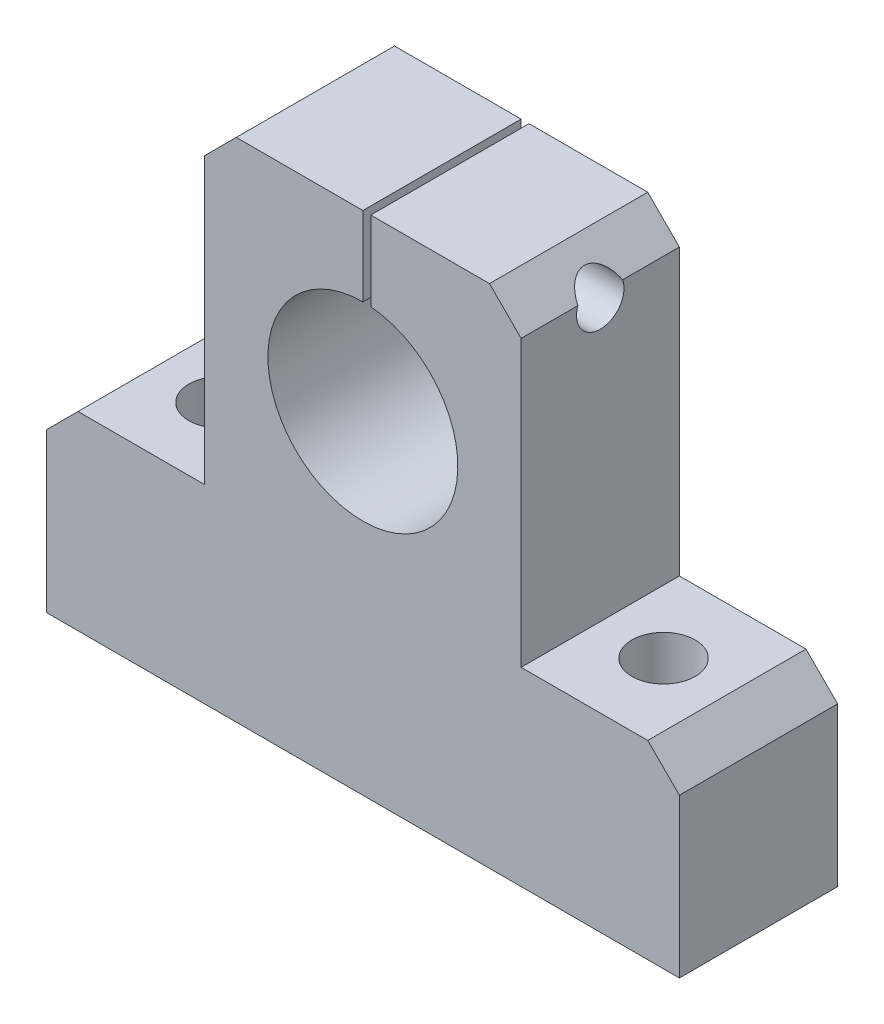
SolidWorks part; units mm, degrees
ref_plane "Front Plane" through (0, 0, 0) normal (0, 0, 1) x (1, 0, 0)
ref_plane "Top Plane" through (0, 0, 0) normal (0, 1, 0) x (1, 0, 0)
ref_plane "Right Plane" through (0, 0, 0) normal (1, 0, 0) x (0, 0, -1)
sketch "Sketch1" plane through (0, 0, 0) normal (0, 0, 1) x (1, 0, 0)
  line L0 (20, 0) -> (-20, 0)
  line L1 (-20, 0) -> (-20, 10)
  line L2 (-18, 12) -> (-10, 12)
  line L3 (-10, 12) -> (-10, 30)
  line L4 (-8, 32) -> (0, 32)
  line L5 (0, 42) -> (0, 0) construction
  line L6 (20, 0) -> (20, 10)
  line L7 (18, 12) -> (10, 12)
  line L8 (10, 12) -> (10, 30)
  line L9 (10, 30) -> (8, 32)
  line L10 (-10, 30) -> (-8, 32)
  line L11 (20, 10) -> (18, 12)
  line L12 (-20, 10) -> (-18, 12)
  line L13 (0.5, 32) -> (0.5, 26.9791)
  line L15 (0, 27) -> (0, 32)
  line L16 (0.5, 32) -> (8, 32)
  arc A0 (0, 27) -> (0.5, 26.9791) centre (0, 21) ccw
  point P3 (-10, 32)
  point P4 (-20, 12)
  point P8 (20, 12)
  point P10 (10, 32)
  dimension "D11" = 12
  dimension "D1" = 20
  dimension "D2" = 40
  dimension "D7" = 20
  dimension "D8" = 12
  dimension "D9" = 21
  dimension "D10" = 0.5
  dimension "D12" = 5
extrude "Boss-Extrude1" add sketch "Sketch1" along normal blind 10
sketch "Sketch2" plane through (-10, 0, 0) normal (-1, 0, 0) x (0, 0, 1)
  line L0 (10, 32) -> (0, 32) construction
  circle A0 centre (5, 29.5) radius 1.5
  dimension "D1" = 3
  dimension "D2" = 2.5
extrude "Cut-Extrude1" cut sketch "Sketch2" against normal through all both and the other way through all
sketch "Sketch3" plane through (0, 12, 0) normal (0, 1, 0) x (1, 0, 0)
  circle A0 centre (14, -5) radius 2
  circle A1 centre (-14, -5) radius 2
  dimension "D1" = 4
  dimension "D2" = 4
extrude "Cut-Extrude2" cut sketch "Sketch3" against normal up to next and the other way through all
